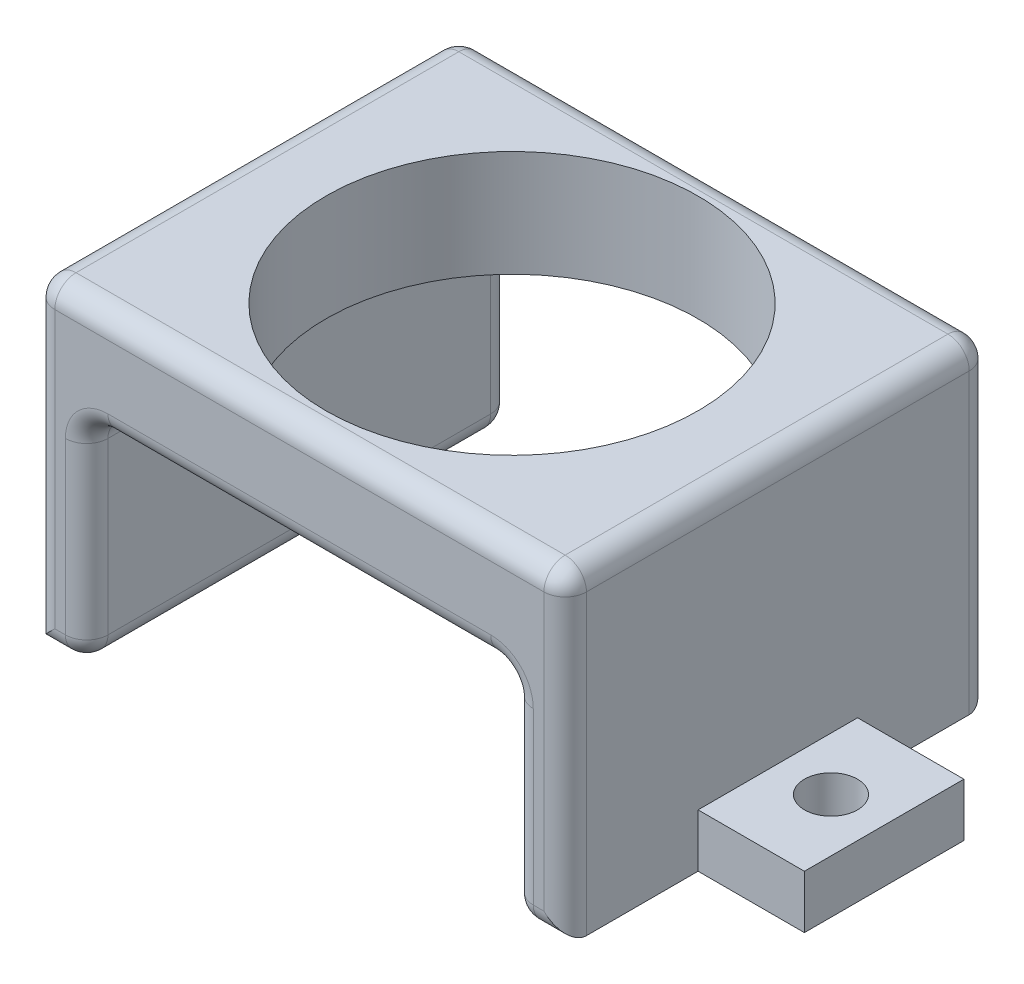
SolidWorks part; units mm, degrees
ref_plane "Front Plane" through (0, 0, 0) normal (0, 0, 1) x (1, 0, 0)
ref_plane "Top Plane" through (0, 0, 0) normal (0, 1, 0) x (1, 0, 0)
ref_plane "Right Plane" through (0, 0, 0) normal (1, 0, 0) x (0, 0, -1)
sketch "Sketch1" plane through (0, 0, 0) normal (0, 1, 0) x (1, 0, 0)
  line L1 (-45, 40) -> (-40, 40)
  line L2 (-45, 40) -> (-45, 0)
  line L3 (-45, 0) -> (-40, 0)
  line L4 (-40, 40) -> (-40, 0)
  line L5 (0, 40) -> (5, 40)
  line L6 (0, 40) -> (0, 0)
  line L7 (0, 0) -> (5, 0)
  line L8 (5, 40) -> (5, 0)
  dimension "D1" = 40
  dimension "D2" = 5
  dimension "D3" = 40
extrude "Boss-Extrude1" add sketch "Sketch1" along normal blind 20
sketch "Sketch2" plane through (0, 20, 0) normal (0, 1, 0) x (1, 0, 0)
  line L1 (-45, 40) -> (5, 40)
  line L2 (-45, 40) -> (-45, 0)
  line L3 (-45, 0) -> (5, 0)
  line L4 (5, 40) -> (5, 0)
  line L5 (-45, 40) -> (-45, 0) construction
  circle A0 centre (-20, 20) radius 17.5
  point P5 (-20, 0)
  point P8 (-45, 20)
  point P15 (-20, 20)
  dimension "D1" = 35
  dimension "D2" = 40
extrude "Boss-Extrude2" add sketch "Sketch2" along normal blind 10
sketch "Sketch3" plane through (0, 0, 0) normal (0, -1, 0) x (1, 0, 0)
  line L11 (-40, 0) -> (-40, -40) construction
  line L12 (-55, -12.5) -> (-40, -12.5)
  line L13 (-55, -12.5) -> (-55, -27.5)
  line L14 (-55, -27.5) -> (-40, -27.5)
  line L15 (-40, -12.5) -> (-40, -27.5)
  line L16 (-45, -40) -> (-45, 0) construction
  line L17 (15, -12.5) -> (0, -12.5)
  line L18 (15, -12.5) -> (15, -27.5)
  line L19 (15, -27.5) -> (0, -27.5)
  line L20 (0, -12.5) -> (0, -27.5)
  line L21 (0, -40) -> (0, 0) construction
  line L22 (5, 0) -> (5, -40) construction
  circle A2 centre (-50, -20) radius 2.5
  circle A3 centre (10, -20) radius 2.5
  point P16 (-55, -20)
  point P17 (15, -20)
  point P18 (15.5235, -19.6479)
  point P21 (-45, -20)
  point P24 (14.4294, -20.7079)
  point P25 (0, -20)
  point P26 (-55.6869, -20)
  dimension "D3" = 15
  dimension "D1" = 5
  dimension "D2" = 5
  dimension "D4" = 15
  dimension "D5" = 15
  dimension "D6" = 15
  dimension "D7" = 5
  dimension "D8" = 5
extrude "Boss-Extrude3" add sketch "Sketch3" against normal blind 5
fillet "Fillet1" radius 2 22 edges at (-45, 15, 0) (-20, 30, 0) (5, 15, 0) (2.5, 0, 0) (0, 10, 0) (-20, 20, 0) (-40, 10, 0) (-42.5, 0, 0) (-40, 10, -40) (-20, 20, -40) (0, 10, -40) (2.5, 0, -40) (5, 15, -40) (-20, 30, -40) (-45, 15, -40) (-42.5, 0, -40) (0, 0, -20) (-40, 0, -20) (0, 20, -20) (5, 30, -20) (-45, 30, -20) (-40, 20, -20)
